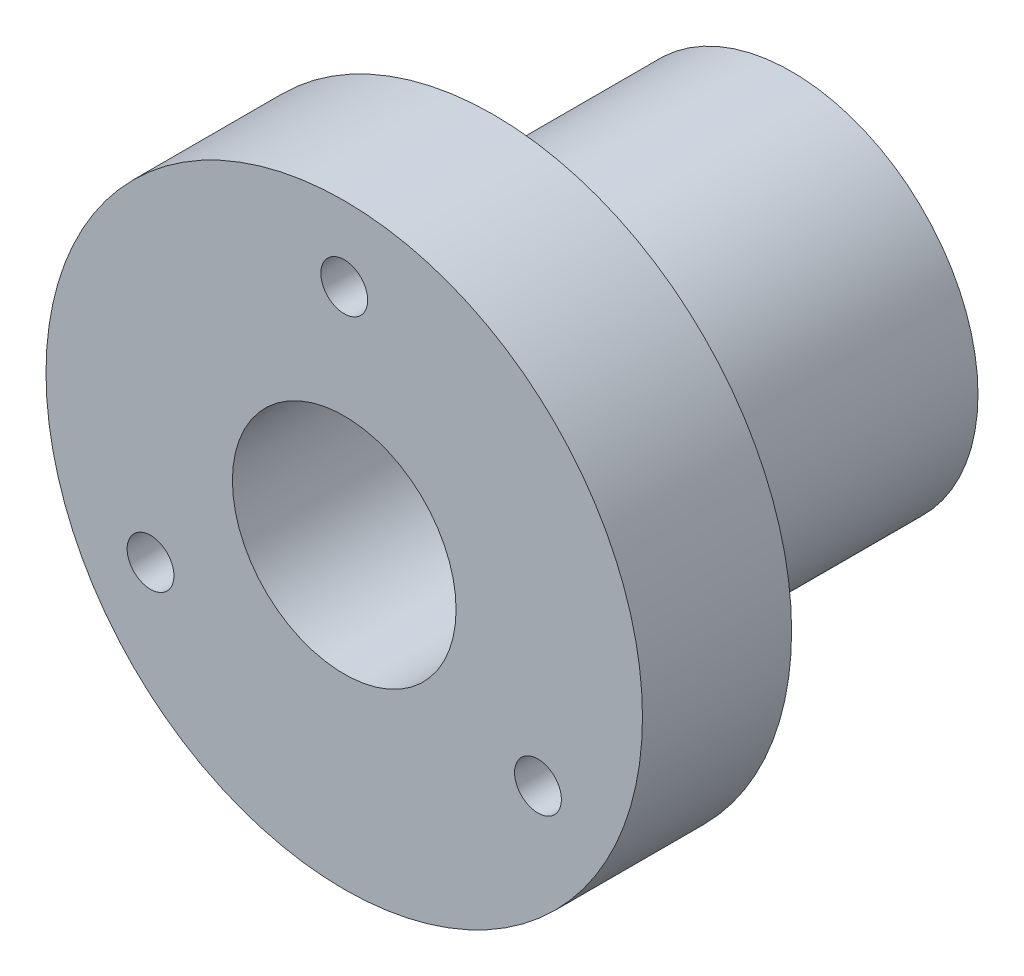
SolidWorks part; units mm, degrees
material "1060 Alloy"
ref_plane "Front" through (0, 0, 0) normal (0, 0, 1) x (1, 0, 0)
ref_plane "Top" through (0, 0, 0) normal (0, 1, 0) x (1, 0, 0)
ref_plane "Right" through (0, 0, 0) normal (1, 0, 0) x (0, 0, -1)
sketch "Sketch1" plane through (0, 0, 0) normal (0, 0, 1) x (1, 0, 0)
  circle A0 centre (0, 0) radius 25.4
  dimension "D1" = 50.8
extrude "Boss-Extrude1" add sketch "Sketch1" against normal blind 12.7
sketch "Sketch9" plane through (0, 0, 0) normal (0, 0, 1) x (1, 0, 0)
  circle A0 centre (0, 0) radius 15.875
  dimension "D1" = 31.75
extrude "Boss-Extrude2" add sketch "Sketch9" against normal blind 38.1
sketch "Sketch10" plane through (0, 0, -12.7) normal (0, 0, -1) x (-1, 0, 0)
  circle A0 centre (0, 0) radius 19.05 construction
  dimension "D1" = 38.1
hole_wizard "#10-24 Tapped Hole1" positions "Sketch11" profile "Sketch12" tap size "#10-24" standard "ANSI Inch" end condition through all
sketch "Sketch11" plane through (0, 0, -12.7) normal (0, 0, -1) x (-1, 0, 0)
  circle A0 centre (0, 0) radius 19.05 construction
  point P0 (0, 19.05)
  point P4 (-16.4978, -9.525)
  point P6 (16.4978, -9.525)
  dimension "D1" = 120
  dimension "D2" = 120
cosmetic thread "Hole Thread4" parameters "D2"=4.826
cosmetic thread "Hole Thread5" parameters "D2"=4.826
cosmetic thread "Hole Thread6" parameters "D2"=4.826
sketch "Sketch12" plane through (0, 19.05, -12.7) normal (1, 0, 0) x (0, 1, 0)
  line L0 (0, 0) -> (0, 12.7)
  line L1 (0, 12.7) -> (1.9939, 12.7)
  line L2 (1.9939, 12.7) -> (1.9939, 0)
  line L5 (1.9939, 0) -> (0, 0)
  line L11 (0, -6.35) -> (0, 107.95) construction
  dimension "Thru Tap Drill Dia." = 3.9878
  dimension "Thru Tap Drill Depth" = 12.7
hole_wizard "Ø8.4 (8.4) Diameter Hole2" positions "Sketch13" profile "Sketch14" hole size "Ø8.4" standard "ANSI Metric" end condition through all
sketch "Sketch13" plane through (0, 0, -38.1) normal (0, 0, -1) x (-1, 0, 0)
  point P0 (0, 0)
sketch "Sketch14" plane through (0, 0, -38.1) normal (1, 0, 0) x (0, 1, 0)
  line L0 (0, 0) -> (0, 38.1)
  line L1 (0, 38.1) -> (4.2, 38.1)
  line L2 (4.2, 38.1) -> (4.2, 0)
  line L5 (4.2, 0) -> (0, 0)
  line L11 (0, -6.35) -> (0, 107.95) construction
  dimension "Thru Hole Dia." = 8.4
  dimension "Thru Hole Depth" = 38.1
hole_wizard "Ø10.0 (10) Diameter Hole1" positions "Sketch15" profile "Sketch16" hole size "Ø10.0" standard "ANSI Metric"
sketch "Sketch15" plane through (0, 0, -38.1) normal (0, 0, -1) x (-1, 0, 0)
  point P0 (0, 0)
sketch "Sketch16" plane through (0, 0, -38.1) normal (1, 0, 0) x (0, 1, 0)
  line L0 (0, 0) -> (0, 13.1643)
  line L1 (0, 13.1643) -> (5, 10.16)
  line L2 (5, 10.16) -> (5, 0)
  line L5 (5, 0) -> (0, 0)
  line L10 (0, 13.1643) -> (-5, 10.16) construction
  line L11 (0, -6.35) -> (0, 107.95) construction
  dimension "Hole Dia." = 10
  dimension "Hole Depth" = 10.16
  dimension "Drill Angle" = 118
hole_wizard "3/4 (0.75) Diameter Hole1" positions "Sketch17" profile "Sketch18" hole size "3/4" standard "ANSI Inch"
sketch "Sketch17" plane through (0, 0, 0) normal (0, 0, 1) x (1, 0, 0)
  point P0 (0, 0)
sketch "Sketch18" plane through (0, 0, 0) normal (1, 0, 0) x (0, -1, 0)
  line L0 (0, 0) -> (0, 22.86)
  line L1 (0, 22.86) -> (9.525, 22.86)
  line L2 (9.525, 22.86) -> (9.525, 0)
  line L5 (9.525, 0) -> (0, 0)
  line L10 (0, 22.86) -> (-9.525, 22.86) construction
  line L11 (0, -6.35) -> (0, 107.95) construction
  dimension "Hole Dia." = 19.05
  dimension "Hole Depth" = 22.86
  dimension "Drill Angle" = 180
